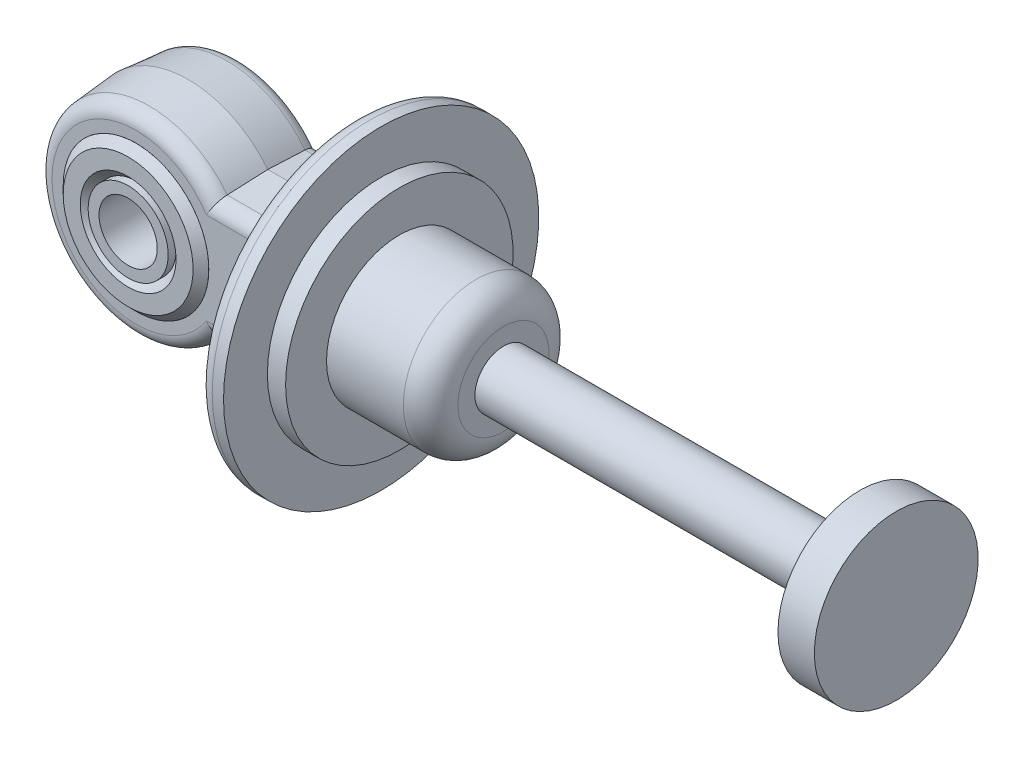
SolidWorks part; units mm, degrees
other "Rod"
other "Rubber"
other "Sleeve"
other "Rubber Stopper"
material "Plain Carbon Steel"
ref_plane "Front Plane" through (0, 0, 0) normal (0, 0, 1) x (1, 0, 0)
ref_plane "Top Plane" through (0, 0, 0) normal (0, 1, 0) x (1, 0, 0)
ref_plane "Right Plane" through (0, 0, 0) normal (1, 0, 0) x (0, 0, -1)
sketch "Sketch1" plane through (0, 0, 0) normal (0, 0, 1) x (1, 0, 0)
  line L1 (3.175, 4.9784) -> (-77.163, 4.9784)
  line L2 (-80.338, 19.8438) -> (-80.338, 27.4955)
  line L3 (-80.338, 27.4955) -> (-84.148, 27.4955)
  line L4 (-88.72, 0) -> (0, 0)
  line L5 (0, 0) -> (90.9428, 0) construction
  line L6 (-80.338, 19.8438) -> (-77.163, 19.8438)
  line L7 (-77.163, 19.8438) -> (-77.163, 4.9784)
  line L8 (3.175, 4.9784) -> (3.175, 14.2875)
  line L9 (3.175, 14.2875) -> (9.525, 14.2875)
  line L10 (9.525, 14.2875) -> (9.525, 0)
  line L11 (9.525, 0) -> (0, 0)
  arc A0 (-84.148, 27.4955) -> (-88.72, 0) centre (-3.7566, 0) ccw
  dimension "D1" = 9.9568
  dimension "D2" = 54.991
  dimension "D3" = 8.382
  dimension "D4" = 3.81
  dimension "D5" = 80.338
  dimension "D6" = 3.175
  dimension "D7" = 39.6875
  dimension "D8" = 3.175
  dimension "D9" = 6.35
  dimension "D10" = 28.575
revolve "Revolve1" add sketch "Sketch1" angle 360 about L5
fillet "Fillet1" radius 2.54 1 edges at (-84.148, 0, 27.4955)
sketch "Sketch2" plane through (0, 0, 0) normal (0, 0, 1) x (1, 0, 0)
  line L0 (-80.338, 11.1125) -> (-100.1135, 11.1125)
  line L1 (-80.338, -27.4955) -> (-80.338, 27.4955) construction
  line L2 (-100.1135, -11.1125) -> (-80.338, -11.1125)
  line L3 (-80.338, -11.1125) -> (-80.338, 11.1125)
  arc A0 (-100.1135, 11.1125) -> (-100.1135, -11.1125) centre (-113.993, 0) ccw
  dimension "D1" = 35.56
  dimension "D2" = 33.655
  dimension "D4" = 22.225
extrude "Boss-Extrude1" add sketch "Sketch2" along normal mid plane 18.2118 draft 5
fillet "Fillet2" radius 2.54 6 edges at (-94.05, -10.3158, -9.1059) (-130.9763, 0, -9.1059) (-94.05, 10.3158, -9.1059) (-94.05, -10.3158, 9.1059) (-130.9763, 0, 9.1059) (-94.05, 10.3158, 9.1059)
fillet "Fillet3" radius 1.27 10 edges at (-87.9604, -10.8154, -3.3956) (-87.7388, -9.8321, -8.3129) (-88.2306, 0, -9.1059) (-87.7448, 9.5728, -8.5511) (-87.9604, -10.8154, 3.3956) (-87.7448, -9.5728, 8.5511) (-88.2306, 0, 9.1059) (-87.7388, 9.8321, 8.3129) (-87.9604, 10.8154, -3.3956) (-87.9604, 10.8154, 3.3956)
sketch "Sketch3" plane through (0, 0, 0) normal (0, 0, 1) x (1, 0, 0)
  circle A0 centre (-113.993, 0) radius 12.7
  dimension "D1" = 25.4
extrude "Cut-Extrude1" cut sketch "Sketch3" against normal through all and the other way through all
sketch "Sketch4" plane through (0, 0, 0) normal (0, 1, 0) x (1, 0, 0)
  line L0 (-101.293, 9.1059) -> (-102.6646, 10.4775)
  line L1 (-102.6646, 10.4775) -> (-105.6364, 10.4775)
  line L2 (-105.6364, 10.4775) -> (-107.008, 9.1059)
  line L3 (-101.293, 9.1059) -> (-126.693, 9.1059) construction
  line L4 (-107.008, 9.1059) -> (-107.008, -9.1059)
  line L5 (-128.6489, -9.1059) -> (-101.7056, -9.1059) construction
  line L6 (-107.008, -9.1059) -> (-105.6364, -10.4775)
  line L7 (-105.6364, -10.4775) -> (-102.6646, -10.4775)
  line L8 (-102.6646, -10.4775) -> (-101.293, -9.1059)
  line L9 (-101.293, -9.1059) -> (-101.293, 9.1059) construction
  line L10 (-101.293, -9.1059) -> (-101.293, 9.1059)
  line L11 (-113.993, 15.282) -> (-113.993, -13.3589) construction
  line L12 (-101.7056, 9.1059) -> (-128.6489, 9.1059) construction
  line L13 (-88.99, -9.1059) -> (-101.7056, -9.1059) construction
  point P22 (-107.008, 0)
  dimension "D1" = 13.97
  dimension "D2" = 20.955
  dimension "D3" = 45
revolve "Revolve2" add sketch "Sketch4" angle 360 about L11
sketch "Sketch5" plane through (0, 0, 0) normal (0, 1, 0) x (1, 0, 0)
  line L0 (-108.913, 10.4775) -> (-108.913, -10.4775)
  line L1 (-122.3496, -10.4775) -> (-105.6364, -10.4775) construction
  line L2 (-108.913, -10.4775) -> (-107.008, -10.4775)
  line L3 (-107.008, -10.4775) -> (-107.008, 10.4775)
  line L4 (-107.008, 10.4775) -> (-108.913, 10.4775)
  line L5 (-105.6364, 10.4775) -> (-122.3496, 10.4775) construction
  line L6 (-107.008, -9.1059) -> (-107.008, 9.1059) construction
  line L7 (-113.993, 15.282) -> (-113.993, -13.3589) construction
  dimension "D1" = 10.16
revolve "Revolve3" add sketch "Sketch5" angle 360 about L7
sketch "Sketch7" plane through (0, 0, 0) normal (0, 0, 1) x (1, 0, 0)
  line L0 (-77.163, 12.7) -> (-63.7645, 12.7)
  line L1 (-77.163, -19.8438) -> (-77.163, 19.8438) construction
  line L2 (-59.002, 7.9375) -> (-59.002, 4.9784)
  line L3 (3.175, 4.9784) -> (-77.163, 4.9784) construction
  line L4 (-59.002, 4.9784) -> (-77.163, 4.9784)
  line L5 (-77.163, 4.9784) -> (-77.163, 12.7)
  line L6 (-80.338, -27.4955) -> (-80.338, 27.4955) construction
  line L7 (0, 0) -> (18.7147, 0) construction
  arc A0 (-63.7645, 12.7) -> (-59.002, 7.9375) centre (-63.7645, 7.9375) cw
  dimension "D1" = 4.7625
  dimension "D2" = 21.336
  dimension "D3" = 25.4
revolve "Revolve4" add sketch "Sketch7" angle 360 about L7
